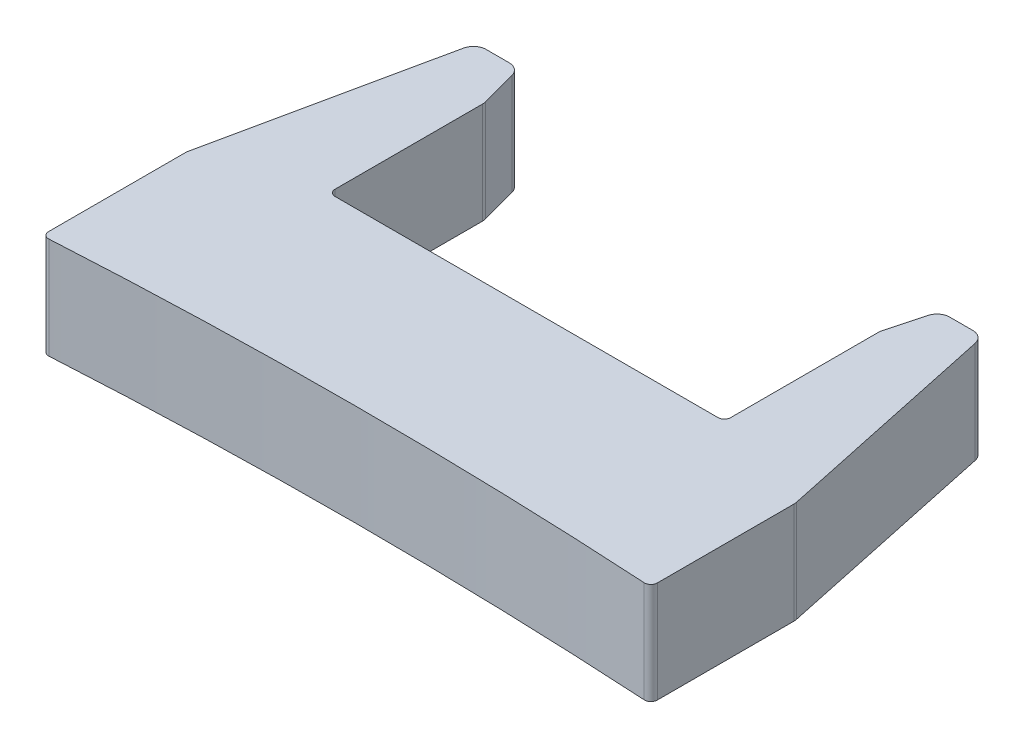
SolidWorks part; units mm, degrees
material "6061-T6 (SS)"
ref_plane "Front Plane" through (0, 0, 0) normal (0, 0, 1) x (1, 0, 0)
ref_plane "Top Plane" through (0, 0, 0) normal (0, 1, 0) x (1, 0, 0)
ref_plane "Right Plane" through (0, 0, 0) normal (1, 0, 0) x (0, 0, -1)
sketch "Sketch1" plane through (0, 0, 0) normal (0, 1, 0) x (1, 0, 0)
  line L0 (-20, 0) -> (0, 0)
  line L1 (24, -2.8) -> (24, -14.2206)
  line L2 (-24, -2.8) -> (-24, -14.2206)
  line L3 (-24, -13.5) -> (24, -13.5) construction
  line L4 (-20, 0) -> (-20, -2.8)
  line L5 (-20, -2.8) -> (-24, -2.8)
  line L6 (20, 0) -> (20, -2.8)
  line L7 (20, -2.8) -> (24, -2.8)
  line L22 (0, 0) -> (20, 0)
  line L25 (-24, -14.2206) -> (0, -413.5) construction
  line L26 (0, -413.5) -> (24, -14.2206) construction
  arc A0 (-24, -14.2206) -> (24, -14.2206) centre (0, -413.5) cw
  dimension "D1" = 13.5
  dimension "D2" = 400
  dimension "D3" = 2.8
  dimension "D4" = 20
  dimension "D5" = 48
extrude "Boss-Extrude1" add sketch "Sketch1" along normal mid plane 8
sketch "Sketch5" plane through (0, 4, 0) normal (0, 1, 0) x (1, 0, 0)
  line L4 (-20, 0) -> (-20, 16) construction
  line L5 (0, 0) -> (0, 18.0283) construction
  line L8 (20, 0) -> (20, 16) construction
  line L17 (-20, 16) -> (-15.6, 16)
  line L19 (-15.6, 16) -> (-15.6, 0)
  line L20 (20, 0) -> (-20, 0) construction
  line L22 (-15.6, 0) -> (-20, 0)
  line L24 (-20, 16) -> (-24, -2.8)
  line L25 (-24, -2.8) -> (-20, -2.8)
  line L26 (-20, -2.8) -> (-20, 0)
  line L27 (20, -2.8) -> (20, 0)
  line L28 (24, -2.8) -> (20, -2.8)
  line L29 (20, 16) -> (24, -2.8)
  line L30 (15.6, 0) -> (20, 0)
  line L31 (15.6, 16) -> (15.6, 0)
  line L32 (20, 16) -> (15.6, 16)
  dimension "D1" = 4.4
  dimension "D2" = 16
extrude "Boss-Extrude2" add sketch "Sketch5" against normal up to surface (8 mm away) up to face at (0, -4, 4.8651)
hole_wizard "M6x1.0 Tapped Hole1" positions "Sketch4" profile "Sketch3" tap size "M6x1.0" standard "ANSI Metric"
sketch "Sketch4" plane through (0, 0, 0) normal (0, 0, -1) x (-1, 0, 0)
  point P0 (0, 0)
cosmetic thread "Hole Thread1" parameters "D1"=6, "D2"=6
sketch "Sketch3" plane through (0, 0, 0) normal (1, 0, 0) x (0, 1, 0)
  line L0 (0, 0) -> (0, 12.5022)
  line L1 (0, 12.5022) -> (2.5, 11)
  line L2 (2.5, 11) -> (2.5, 0)
  line L5 (2.5, 0) -> (0, 0)
  line L10 (0, 12.5022) -> (-2.5, 11) construction
  line L11 (0, -6.35) -> (0, 107.95) construction
  dimension "Tap Drill Dia." = 5
  dimension "Tap Drill Depth" = 11
  dimension "Drill Angle" = 118
chamfer "Chamfer1" distance 1 angle 75 2 edges at (-15.6, 0, -16) (15.6, 0, -16)
fillet "Fillet1" radius 1 8 edges at (-15.6, 0, -12.2679) (-16.6, 0, -16) (20, 0, -16) (24, 0, 2.8) (-24, 0, 2.8) (-20, 0, -16) (16.6, 0, -16) (15.6, 0, -12.2679)
fillet "Fillet2" radius 0.5 4 edges at (-24, 0, 14.2206) (24, 0, 14.2206) (-15.6, 0, 0) (15.6, 0, 0)
